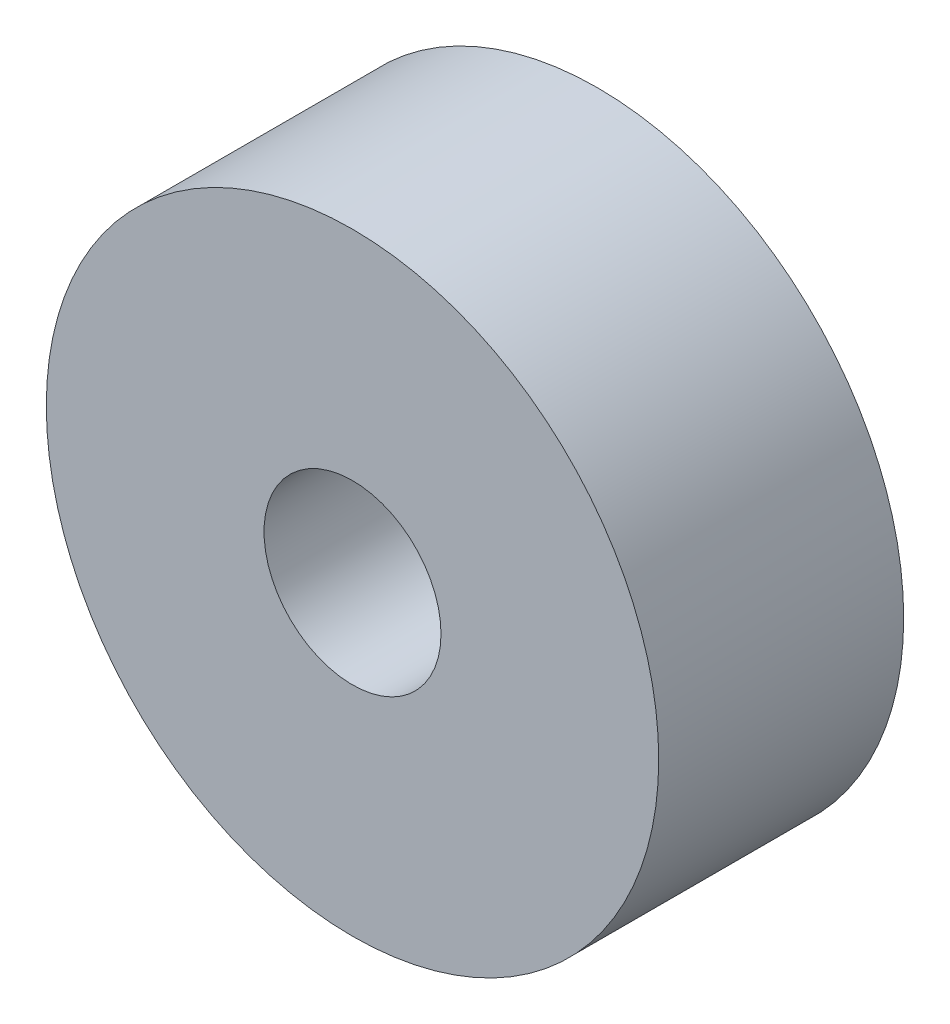
SolidWorks part; units mm, degrees
material "Plain Carbon Steel"
ref_plane "Front Plane" through (0, 0, 0) normal (0, 0, 1) x (1, 0, 0)
ref_plane "Top Plane" through (0, 0, 0) normal (0, 1, 0) x (1, 0, 0)
ref_plane "Right Plane" through (0, 0, 0) normal (1, 0, 0) x (0, 0, -1)
sketch "Sketch1" plane through (0, 0, 0) normal (0, 0, 1) x (1, 0, 0)
  circle A0 centre (-4.0775, 1.2496) radius 5
  circle A1 centre (-4.0775, 1.2496) radius 1.445
  dimension "D1" = 10
extrude "Boss-Extrude2" add sketch "Sketch1" along normal blind 4
